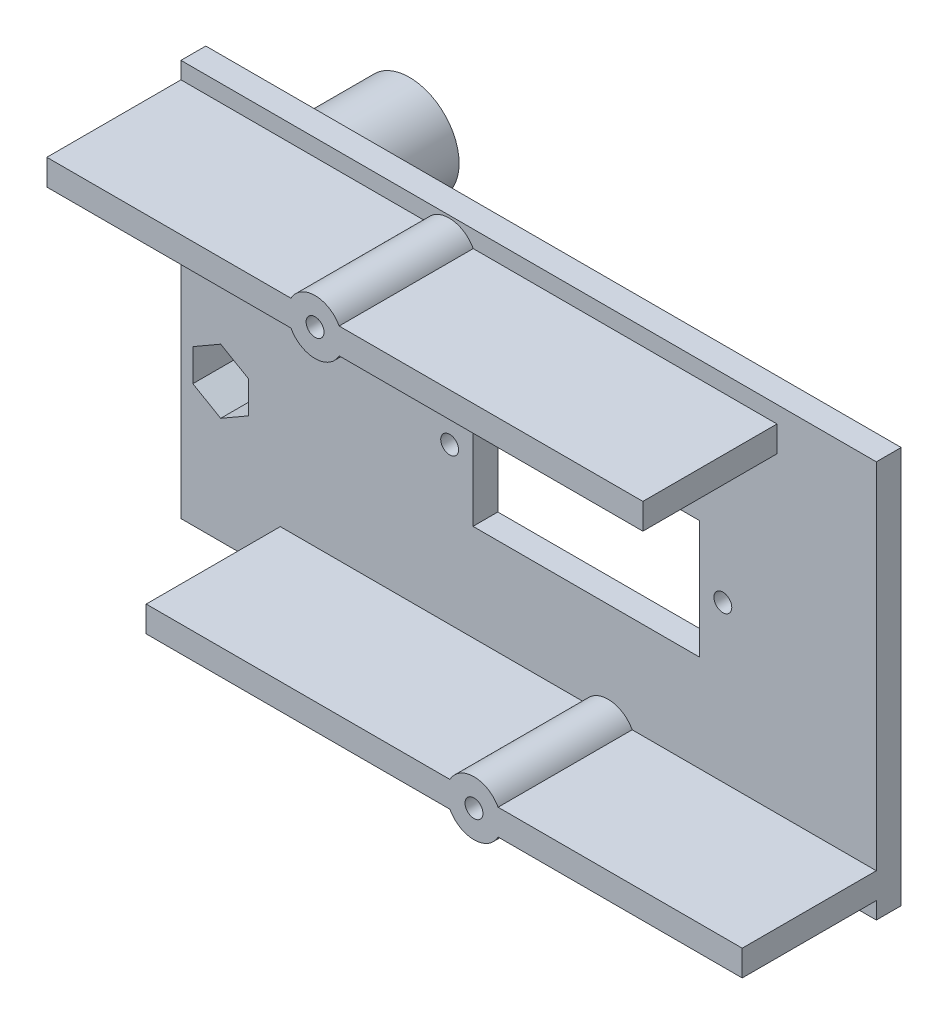
SolidWorks part; units mm, degrees
ref_plane "Front Plane" through (0, 0, 0) normal (0, 0, 1) x (1, 0, 0)
ref_plane "Top Plane" through (0, 0, 0) normal (0, 1, 0) x (1, 0, 0)
ref_plane "Right Plane" through (0, 0, 0) normal (1, 0, 0) x (0, 0, -1)
sketch "Sketch1" plane through (0, 0, 0) normal (0, 0, 1) x (1, 0, 0)
  line L0 (-35, -19.975) -> (35, -19.975)
  line L1 (35, -19.975) -> (35, 19.975)
  line L2 (35, 19.975) -> (-35, 19.975)
  line L3 (-35, 19.975) -> (-35, -19.975)
extrude "Boss-Extrude1" add sketch "Sketch1" along normal blind 2.5 from offset 2.5
sketch "Sketch2" plane through (0, 0, 0) normal (0, 0, 1) x (1, 0, 0)
  line L0 (-35, 15.675) -> (25, 15.675)
  line L1 (25, 15.675) -> (25, 18.275)
  line L2 (25, 18.275) -> (-35, 18.275)
  line L3 (-35, 18.275) -> (-35, 15.675)
extrude "Boss-Extrude2" add sketch "Sketch2" along normal blind 13.5
sketch "Sketch3" plane through (0, 0, 0) normal (0, 0, 1) x (1, 0, 0)
  line L0 (-25, -18.275) -> (35, -18.275)
  line L1 (35, -18.275) -> (35, -15.675)
  line L2 (35, -15.675) -> (-25, -15.675)
  line L3 (-25, -15.675) -> (-25, -18.275)
extrude "Boss-Extrude3" add sketch "Sketch3" along normal blind 13.5
sketch "Sketch4" plane through (0, 0, 0) normal (0, 0, 1) x (1, 0, 0)
  circle A0 centre (-8, 16.975) radius 2.75
  circle A1 centre (8, -16.975) radius 2.75
extrude "Boss-Extrude4" add sketch "Sketch4" along normal blind 13.5
sketch "Sketch5" plane through (0, 0, 0) normal (0, 0, 1) x (1, 0, 0)
  circle A0 centre (-31, 6) radius 5
  circle A1 centre (-31, -6) radius 5
extrude "Boss-Extrude5" add sketch "Sketch5" along normal blind 16.5 from offset 19
sketch "Sketch6" plane through (0, 0, 0) normal (0, 0, 1) x (1, 0, 0)
  line L0 (-5.6, -5.95) -> (17.2, -5.95)
  line L1 (17.2, -5.95) -> (17.2, 5.95)
  line L2 (17.2, 5.95) -> (-5.6, 5.95)
  line L3 (-5.6, 5.95) -> (-5.6, -5.95)
extrude "Cut-Extrude1" cut sketch "Sketch6" against normal through all and the other way through all
sketch "Sketch7" plane through (0, 0, 0) normal (0, 0, 1) x (1, 0, 0)
  circle A0 centre (-7.95, 0) radius 0.9
  circle A1 centre (19.55, 0) radius 0.9
extrude "Cut-Extrude2" cut sketch "Sketch7" against normal through all and the other way through all
sketch "Sketch8" plane through (0, 0, 0) normal (0, 0, 1) x (1, 0, 0)
  circle A0 centre (-8, 16.975) radius 0.9
  circle A1 centre (8, -16.975) radius 0.9
extrude "Cut-Extrude3" cut sketch "Sketch8" against normal through all and the other way through all
sketch "Sketch9" plane through (0, 0, 0) normal (0, 0, 1) x (1, 0, 0)
  circle A0 centre (-31, 6) radius 1.725
  circle A1 centre (-31, -6) radius 1.725
extrude "Cut-Extrude4" cut sketch "Sketch9" against normal through all and the other way through all
sketch "Sketch10" plane through (0, 0, 0) normal (0, 0, 1) x (1, 0, 0)
  line L0 (-28.2, 7.6166) -> (-31, 9.2332)
  line L1 (-31, 9.2332) -> (-33.8, 7.6166)
  line L2 (-33.8, 7.6166) -> (-33.8, 4.3834)
  line L3 (-33.8, 4.3834) -> (-31, 2.7668)
  line L4 (-31, 2.7668) -> (-28.2, 4.3834)
  line L5 (-28.2, 4.3834) -> (-28.2, 7.6166)
  line L6 (-28.2, -4.3834) -> (-31, -2.7668)
  line L7 (-31, -2.7668) -> (-33.8, -4.3834)
  line L8 (-33.8, -4.3834) -> (-33.8, -7.6166)
  line L9 (-33.8, -7.6166) -> (-31, -9.2332)
  line L10 (-31, -9.2332) -> (-28.2, -7.6166)
  line L11 (-28.2, -7.6166) -> (-28.2, -4.3834)
extrude "Cut-Extrude5" cut sketch "Sketch10" along normal blind 4.2 from offset 4.2
